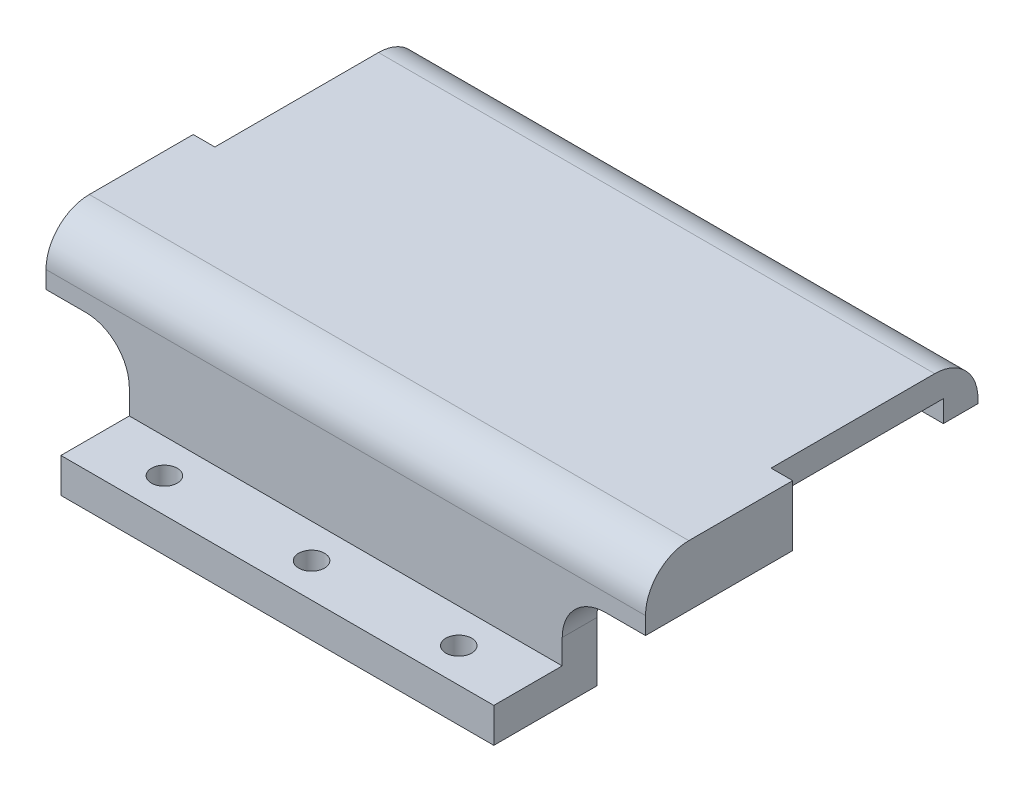
SolidWorks part; units mm, degrees
ref_plane "Front Plane" through (0, 0, 0) normal (0, 0, 1) x (1, 0, 0)
ref_plane "Top Plane" through (0, 0, 0) normal (0, 1, 0) x (1, 0, 0)
ref_plane "Right Plane" through (0, 0, 0) normal (1, 0, 0) x (0, 0, -1)
sketch "Sketch1" plane through (0, 0, 0) normal (0, 1, 0) x (1, 0, 0)
  line L1 (-40.7924, -25.9715) -> (40.7924, -25.9715)
  line L2 (-40.7924, -25.9715) -> (-40.7924, 25.9715)
  line L3 (-40.7924, 25.9715) -> (40.7924, 25.9715)
  line L4 (40.7924, -25.9715) -> (40.7924, 25.9715)
  line L5 (-40.7924, -25.9715) -> (40.7924, 25.9715) construction
  line L6 (-40.7924, 25.9715) -> (40.7924, -25.9715) construction
  point P0 (0, 0)
  dimension "D1" = 51.943
  dimension "D2" = 81.5848
extrude "Boss-Extrude1" add sketch "Sketch1" along normal blind 3.81
sketch "Sketch2" plane through (0, 0, 0) normal (0, -1, 0) x (1, 0, 0)
  line L1 (-31.75, 25.9715) -> (31.75, 25.9715)
  line L2 (-31.75, 25.9715) -> (-31.75, 20.8915)
  line L3 (-31.75, 20.8915) -> (31.75, 20.8915)
  line L4 (31.75, 25.9715) -> (31.75, 20.8915)
  line L5 (0, 25.9715) -> (0, -25.9715) construction
  line L6 (40.7924, -25.9715) -> (-40.7924, -25.9715) construction
  line L7 (-40.7924, 25.9715) -> (40.7924, 25.9715) construction
  dimension "D1" = 5.08
  dimension "D2" = 63.5
extrude "Boss-Extrude2" add sketch "Sketch2" along normal blind 20.1168
sketch "Sketch3" plane through (0, 0, 0) normal (0, -1, 0) x (1, 0, 0)
  line L0 (40.7924, 25.9715) -> (40.7924, -25.9715) construction
  line L1 (-40.7924, -25.9715) -> (40.7924, -25.9715)
  line L2 (-40.7924, -25.9715) -> (-40.7924, -20.8915)
  line L3 (-40.7924, -20.8915) -> (40.7924, -20.8915)
  line L4 (40.7924, -25.9715) -> (40.7924, -20.8915)
  dimension "D1" = 5.08
extrude "Boss-Extrude3" add sketch "Sketch3" along normal blind 3.175
sketch "Sketch4" plane through (0, 0, 25.9715) normal (0, 0, 1) x (1, 0, 0)
  line L1 (-31.75, -20.1168) -> (31.75, -20.1168)
  line L2 (-31.75, -20.1168) -> (-31.75, -15.0368)
  line L3 (-31.75, -15.0368) -> (31.75, -15.0368)
  line L4 (31.75, -20.1168) -> (31.75, -15.0368)
  line L5 (-31.75, -20.1168) -> (-31.75, 0) construction
  line L6 (31.75, -20.1168) -> (31.75, 0) construction
  line L7 (31.75, -20.1168) -> (-31.75, -20.1168) construction
  dimension "D1" = 5.08
extrude "Boss-Extrude4" add sketch "Sketch4" along normal blind 10.033
sketch "Sketch6" plane through (0, 3.81, 0) normal (0, 1, 0) x (1, 0, 0)
  line L1 (-40.7924, -25.9715) -> (-43.9674, -25.9715)
  line L2 (-40.7924, -25.9715) -> (-40.7924, -4.3815)
  line L3 (-40.7924, -4.3815) -> (-43.9674, -4.3815)
  line L4 (-43.9674, -25.9715) -> (-43.9674, -4.3815)
  line L5 (40.7924, -25.9715) -> (43.9674, -25.9715)
  line L6 (40.7924, -25.9715) -> (40.7924, -4.3815)
  line L7 (40.7924, -4.3815) -> (43.9674, -4.3815)
  line L8 (43.9674, -25.9715) -> (43.9674, -4.3815)
  dimension "D1" = 3.175
  dimension "D2" = 3.175
  dimension "D3" = 21.59
extrude "Boss-Extrude5" add sketch "Sketch6" against normal blind 8.89
fillet "Fillet1" radius 6.35 1 edges at (0, 3.81, -25.9715)
sketch "Sketch7" plane through (0, 0, 25.9715) normal (0, 0, 1) x (1, 0, 0)
  line L1 (40.7924, -5.08) -> (31.75, -5.08)
  line L2 (40.7924, -5.08) -> (40.7924, 0)
  line L3 (40.7924, 0) -> (31.75, 0)
  line L4 (31.75, -5.08) -> (31.75, 0)
  line L5 (-40.7924, -5.08) -> (-31.75, -5.08)
  line L6 (-40.7924, -5.08) -> (-40.7924, 0)
  line L7 (-40.7924, 0) -> (-31.75, 0)
  line L8 (-31.75, -5.08) -> (-31.75, 0)
extrude "Boss-Extrude6" add sketch "Sketch7" against normal up to surface (5.08 mm away) up to face at (0, -10.0584, 20.8915)
fillet "Fillet2" radius 6.35 2 edges at (-31.75, -5.08, 23.4315) (31.75, -5.08, 23.4315)
fillet "Fillet3" radius 6.35 1 edges at (0, 3.81, 25.9715)
sketch "Sketch8" plane through (0, 0, 0) normal (0, -1, 0) x (1, 0, 0)
  line L0 (0, 20.8915) -> (0, -20.8915) construction
  line L1 (-31.75, 20.8915) -> (31.75, 20.8915) construction
  line L2 (40.7924, -20.8915) -> (-40.7924, -20.8915) construction
  line L3 (-40.7924, 20.8915) -> (40.7924, 20.8915) construction
  line L4 (-0.635, 20.8915) -> (0.635, 20.8915)
  line L5 (-0.635, 20.8915) -> (-0.635, -20.8915)
  line L6 (-0.635, -20.8915) -> (0.635, -20.8915)
  line L7 (0.635, 20.8915) -> (0.635, -20.8915)
  line L8 (40.7924, -20.8915) -> (-40.7924, -20.8915) construction
  dimension "D1" = 1.27
extrude "Boss-Extrude7" add sketch "Sketch8" along normal up to surface (3.175 mm away) up to face at (0, -3.175, -23.4315)
hole_wizard "#6 Clearance Hole1" positions "3DSketch3" profile "Sketch9" hole size "#6" standard "ANSI Inch" end condition through all
sketch3d "3DSketch3"
  line L0 (-31.75, -15.0368, 30.988) -> (31.75, -15.0368, 30.988) construction
  line L1 (-31.75, -15.0368, 36.0045) -> (-31.75, -15.0368, 25.9715) construction
  line L2 (31.75, -15.0368, 36.0045) -> (31.75, -15.0368, 25.9715) construction
  point P8 (-21.59, -15.0368, 30.988)
  point P10 (0, -15.0368, 30.988)
  point P12 (21.59, -15.0368, 30.988)
  dimension "D2" = 10.16
  dimension "D1" = 10.16
sketch "Sketch9" plane through (21.59, -15.0368, 30.988) normal (1, 0, 0) x (0, 0, 1)
  line L0 (0, 0) -> (0, 5.08)
  line L1 (0, 5.08) -> (1.8986, 5.08)
  line L2 (1.8986, 5.08) -> (1.8986, 0)
  line L5 (1.8986, 0) -> (0, 0)
  line L11 (0, -6.35) -> (0, 107.95) construction
  dimension "Thru Hole Dia." = 3.7973
  dimension "Thru Hole Depth" = 5.08
equation "\"D2@Sketch6\"=\"D1@Sketch6\""
equation "\"D2@3DSketch3\"=\"D1@3DSketch3\""
